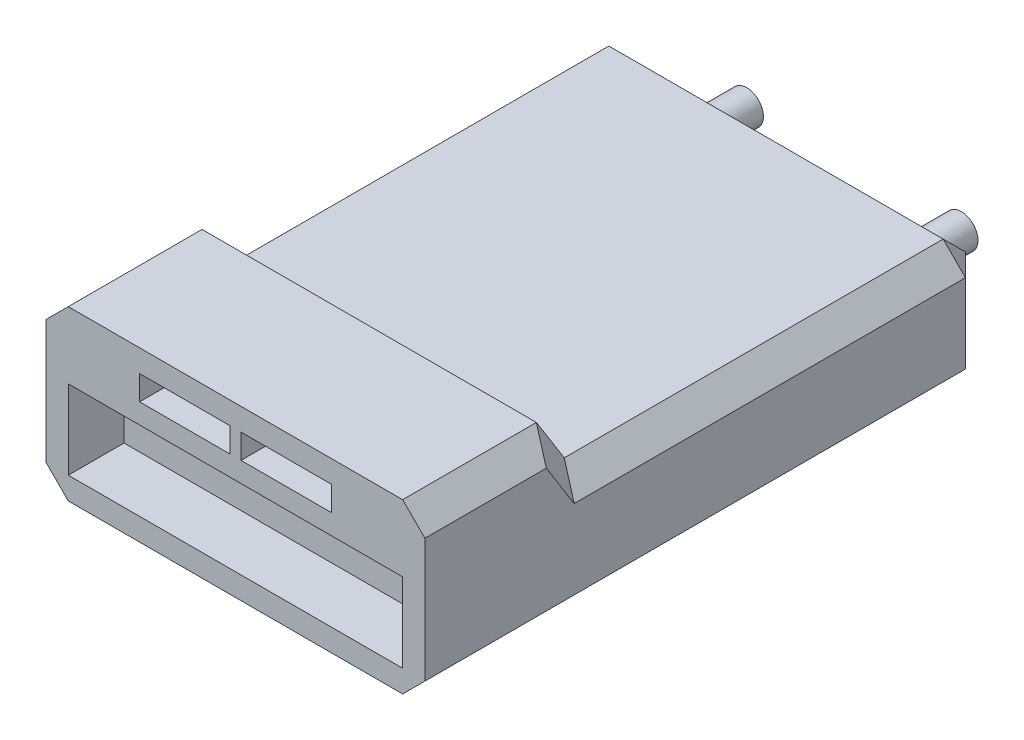
SolidWorks part; units mm, degrees
material "ABS"
ref_plane "Front" through (0, 0, 0) normal (0, 0, 1) x (1, 0, 0)
ref_plane "Top" through (0, 0, 0) normal (0, 1, 0) x (1, 0, 0)
ref_plane "Right" through (0, 0, 0) normal (1, 0, 0) x (0, 0, -1)
sketch "Sketch1" plane through (0, 0, 0) normal (1, 0, 0) x (0, 0, -1)
  line L0 (0, 0) -> (50.5, 0)
  line L1 (50.5, 0) -> (50.5, 11.1)
  line L2 (50.5, 11.1) -> (14.5, 11.1)
  line L3 (14.5, 11.1) -> (12, 15.1)
  line L4 (12, 15.1) -> (0, 15.1)
  line L5 (0, 15.1) -> (0, 0)
  dimension "D1" = 50.5
  dimension "D2" = 11.1
  dimension "D3" = 36
  dimension "D4" = 15.1
  dimension "D5" = 12
extrude "Boss-Extrude1" add sketch "Sketch1" along normal mid plane 34
sketch "Sketch2" plane through (0, 0, -50.5) normal (0, 0, -1) x (-1, 0, 0)
  line L0 (-9.625, 5.55) -> (9.625, 5.55) construction
  line L1 (-17, 0) -> (17, 0) construction
  line L2 (17, 0) -> (17, 11.1) construction
  circle A0 centre (9.625, 5.55) radius 1.5
  circle A1 centre (-9.625, 5.55) radius 1.5
  point P4 (0, 5.55)
  point P7 (0, 0)
  point P10 (17, 5.55)
  dimension "D1" = 3
  dimension "D2" = 19.25
extrude "Boss-Extrude2" add sketch "Sketch2" along normal blind 5
sketch "Sketch3" plane through (0, 0, 0) normal (0, 0, 1) x (1, 0, 0)
  line L0 (-15, 9.1) -> (-17, 9.1) construction
  line L1 (-15, 9.1) -> (15, 9.1)
  line L2 (-15, 9.1) -> (-15, 2)
  line L3 (-15, 2) -> (15, 2)
  line L4 (15, 9.1) -> (15, 2)
  line L5 (-17, 15.1) -> (-17, 0) construction
  line L6 (17, 15.1) -> (-17, 15.1) construction
  line L8 (15, 2) -> (15, 0) construction
  line L9 (17, 0) -> (-17, 0) construction
  line L10 (15, 2) -> (17, 2) construction
  line L11 (17, 15.1) -> (17, 0) construction
  line L12 (0.5, 10.9) -> (-0.5, 10.9) construction
  line L13 (-8.6, 13.1) -> (-0.5, 13.1)
  line L14 (-8.6, 13.1) -> (-8.6, 10.9)
  line L15 (-8.6, 10.9) -> (-0.5, 10.9)
  line L16 (-0.5, 13.1) -> (-0.5, 10.9)
  line L17 (0.5, 13.1) -> (8.6, 13.1)
  line L18 (0.5, 13.1) -> (0.5, 10.9)
  line L19 (0.5, 10.9) -> (8.6, 10.9)
  line L20 (8.6, 13.1) -> (8.6, 10.9)
  line L21 (-0.5, 13.1) -> (-0.5, 15.1) construction
  point P23 (0, 10.9)
  point P24 (0, 9.1)
  dimension "D1" = 2
  dimension "D2" = 6
  dimension "D3" = 1
  dimension "D4" = 8.4
  dimension "D5" = 2.2
extrude "Cut-Extrude1" cut sketch "Sketch3" against normal blind 5
chamfer "Chamfer1" distance 2 angle 45 12 edges at (-17, 5.55, -50.5) (-17, 0, -25.25) (0, 0, -50.5) (17, 0, -25.25) (17, 5.55, -50.5) (-17, 15.1, -6) (-17, 13.1, -13.25) (17, 15.1, -6) (17, 13.1, -13.25) (-17, 11.1, -32.5) (0, 11.1, -50.5) (17, 11.1, -32.5)
